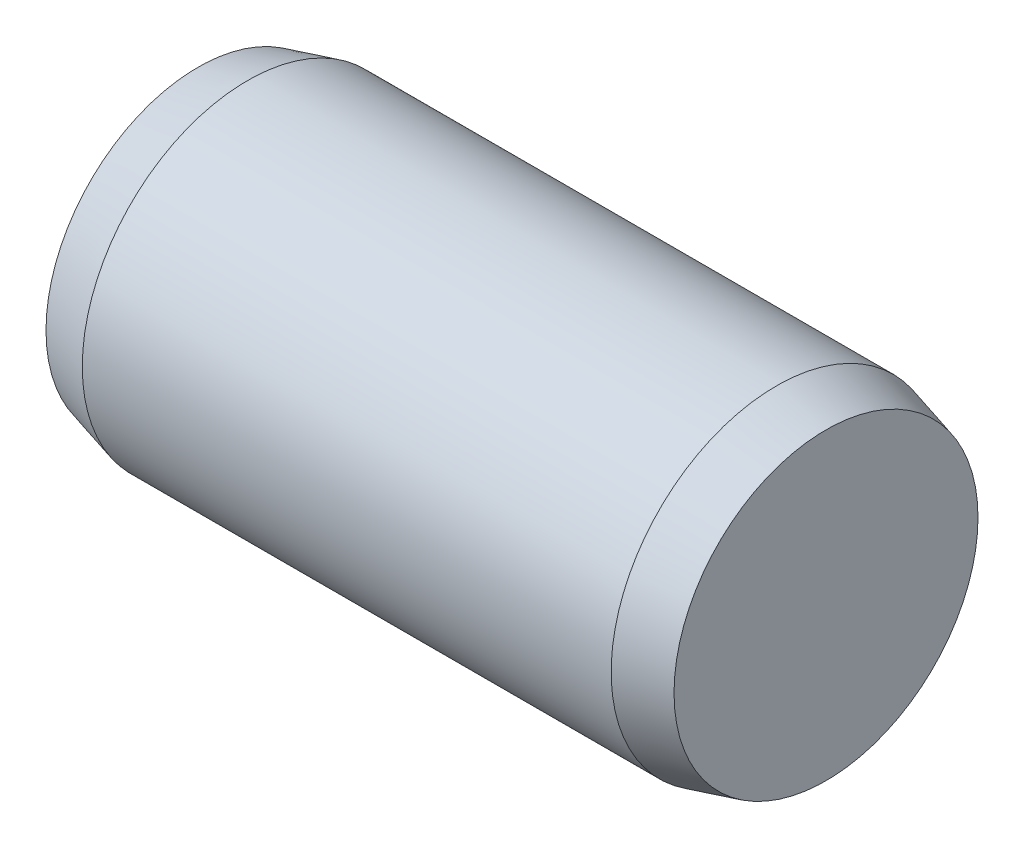
SolidWorks part; units mm, degrees
ref_plane "Front Plane" through (0, 0, 0) normal (0, 0, 1) x (1, 0, 0)
ref_plane "Top Plane" through (0, 0, 0) normal (0, 1, 0) x (1, 0, 0)
ref_plane "Right Plane" through (0, 0, 0) normal (1, 0, 0) x (0, 0, -1)
sketch "Sketch1" plane through (0, 0, 0) normal (0, 0, 1) x (1, 0, 0)
  line L0 (-4, 0) -> (4, 0) construction
  line L1 (4, 2.5) -> (4, -2.5) construction
  line L2 (-4, 2.5) -> (-4, -2.5) construction
  line L3 (4.75, 2.5) -> (4.75, -2.5) construction
  line L4 (-4.75, 2.5) -> (-4.75, -2.5) construction
  line L5 (-4, 0) -> (-4.75, 0) construction
  line L6 (4, 0) -> (4.75, 0) construction
  dimension "D1" = 0.75
  dimension "Dia" = 5
  dimension "Length" = 8
  dimension "C" = 0.75
sketch "Sketch2" plane through (0, 0, 0) normal (1, 0, 0) x (0, 0, -1)
  circle A0 centre (0, 0) radius 2.5
extrude "Extrude1" add sketch "Sketch2" against normal up to vertex (4 mm away) and the other way up to vertex (4 mm away) up to point (-4, 2.5, 0) other way up to point (4, 2.5, 0)
sketch "Sketch3" plane through (4, 0, 0) normal (1, 0, 0) x (0, 0, -1)
  circle A1 centre (0, 0) radius 2.5
  circle A2 centre (0, 0) radius 2.5
  dimension "D1" = 0
extrude "Extrude2" add sketch "Sketch3" along normal up to vertex (0.75 mm away) draft 15 up to point (4.75, 0, 0)
sketch "Sketch4" plane through (-4, 0, 0) normal (-1, 0, 0) x (0, 0, 1)
  circle A1 centre (0, 0) radius 2.5
  circle A2 centre (0, 0) radius 2.5
  dimension "D1" = 0
extrude "Extrude3" add sketch "Sketch4" along normal up to vertex (0.75 mm away) draft 15 up to point (-4.75, 0, 0)
equation "\"D1@Sketch1\" = \"C@Sketch1\""
